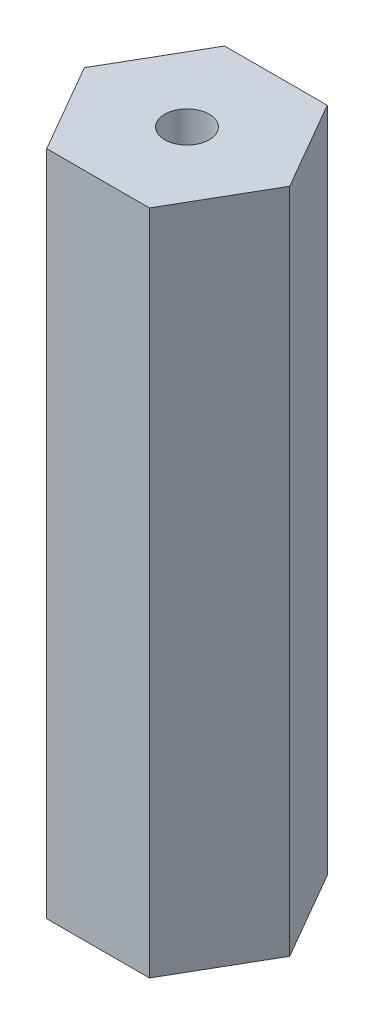
SolidWorks part; units mm, degrees
material "Brass"
ref_plane "Front Plane" through (0, 0, 0) normal (0, 0, 1) x (1, 0, 0)
ref_plane "Top Plane" through (0, 0, 0) normal (0, 1, 0) x (1, 0, 0)
ref_plane "Right Plane" through (0, 0, 0) normal (1, 0, 0) x (0, 0, -1)
sketch "Sketch1" plane through (0, 0, 0) normal (0, 1, 0) x (1, 0, 0)
  line L1 (-14.6647, 0) -> (-7.3323, -12.7)
  line L2 (-7.3323, -12.7) -> (7.3323, -12.7)
  line L3 (7.3323, -12.7) -> (14.6647, 0)
  line L4 (14.6647, 0) -> (7.3323, 12.7)
  line L5 (7.3323, 12.7) -> (-7.3323, 12.7)
  line L6 (-7.3323, 12.7) -> (-14.6647, 0)
  circle A0 centre (0, 0) radius 12.7 construction
  dimension "D1" = 25.4
extrude "Boss-Extrude1" add sketch "Sketch1" along normal mid plane 95.25
sketch "Sketch2" plane through (0, 47.625, 0) normal (0, 1, 0) x (1, 0, 0)
  circle A0 centre (0, 0) radius 3.175
  dimension "D1" = 6.35
extrude "Cut-Extrude1" cut sketch "Sketch2" against normal through all
